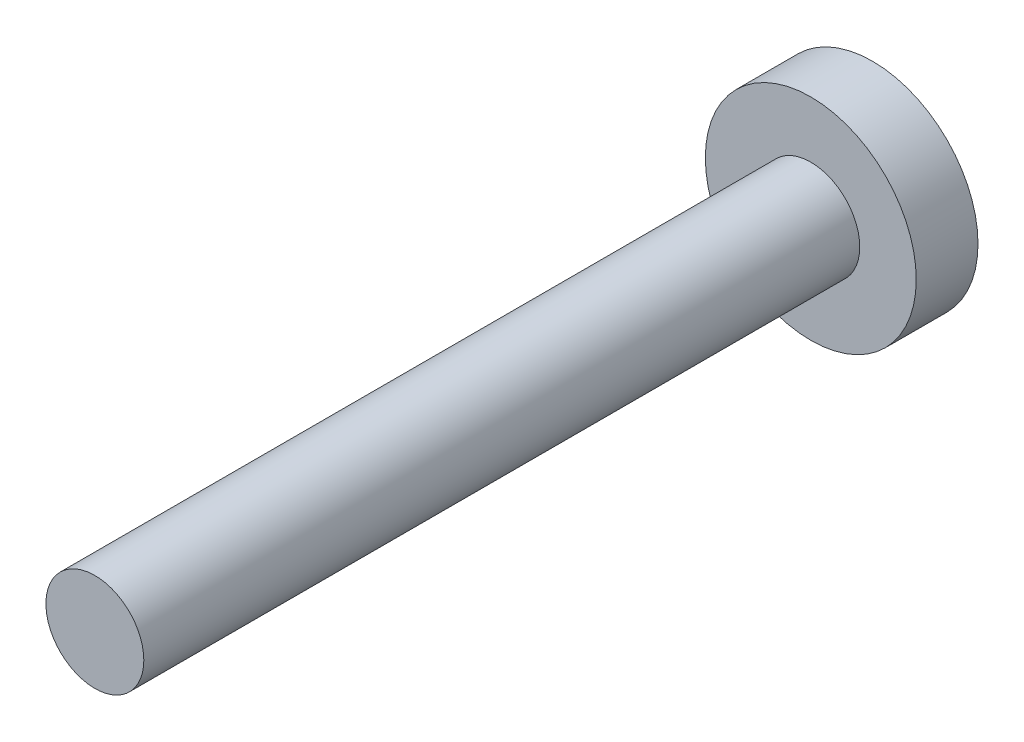
SolidWorks part; units mm, degrees
ref_plane "Front Plane" through (0, 0, 0) normal (0, 0, 1) x (1, 0, 0)
ref_plane "Top Plane" through (0, 0, 0) normal (0, 1, 0) x (1, 0, 0)
ref_plane "Right Plane" through (0, 0, 0) normal (1, 0, 0) x (0, 0, -1)
sketch "Sketch1" plane through (0, 0, 0) normal (0, 0, 1) x (1, 0, 0)
  circle A0 centre (0, 0) radius 6.1125
  dimension "D1" = 12.225
extrude "Boss-Extrude1" add sketch "Sketch1" along normal blind 3.58
sketch "Sketch2" plane through (0, 0, 3.58) normal (0, 0, 1) x (1, 0, 0)
  circle A0 centre (0, 0) radius 2.8375
  dimension "D1" = 5.675
extrude "Boss-Extrude2" add sketch "Sketch2" along normal blind 41.5
